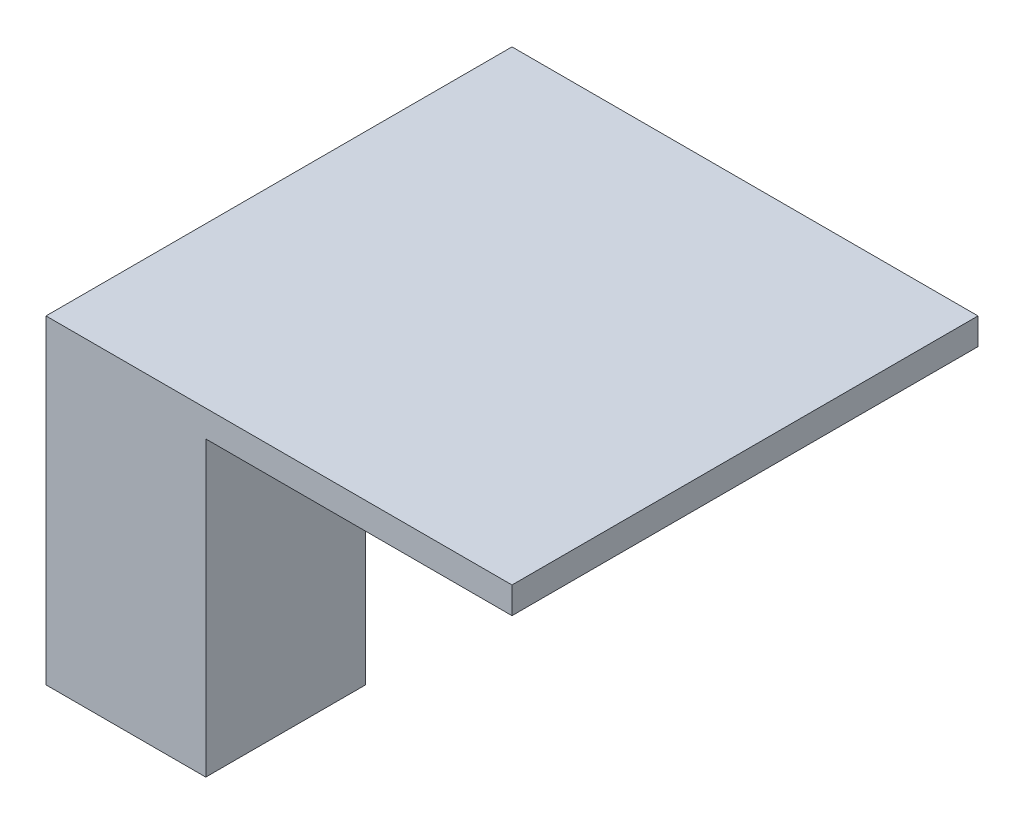
SolidWorks part; units mm, degrees
ref_plane "Front Plane" through (0, 0, 0) normal (0, 0, 1) x (1, 0, 0)
ref_plane "Top Plane" through (0, 0, 0) normal (0, 1, 0) x (1, 0, 0)
ref_plane "Right Plane" through (0, 0, 0) normal (1, 0, 0) x (0, 0, -1)
sketch "Sketch1" plane through (0, 0, 0) normal (0, 1, 0) x (1, 0, 0)
  line L1 (0, 0) -> (12, 0)
  line L2 (0, 0) -> (0, 12)
  line L3 (0, 12) -> (12, 12)
  line L4 (12, 0) -> (12, 12)
  dimension "D1" = 12
extrude "Boss-Extrude1" add sketch "Sketch1" along normal blind 22
sketch "Sketch2" plane through (0, 22, 0) normal (0, 1, 0) x (1, 0, 0)
  line L1 (0, 0) -> (35, 0)
  line L2 (0, 0) -> (0, 35)
  line L3 (0, 35) -> (35, 35)
  line L4 (35, 0) -> (35, 35)
  dimension "D1" = 35
extrude "Boss-Extrude2" add sketch "Sketch2" along normal blind 2
